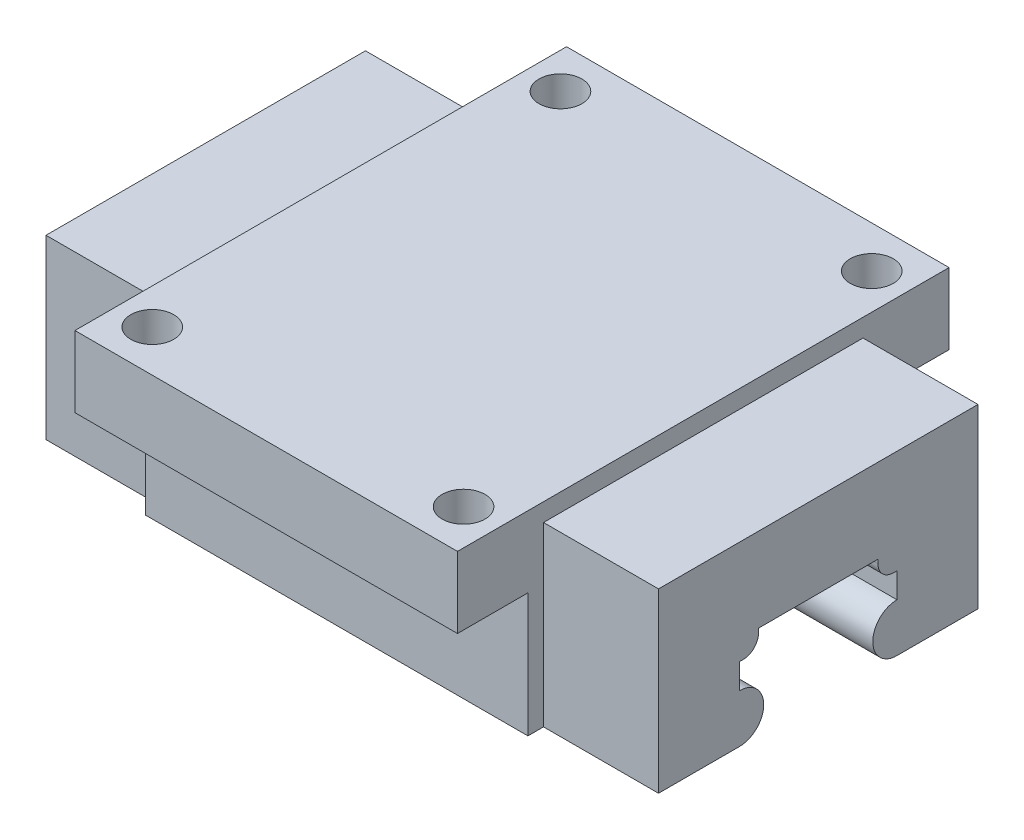
SolidWorks part; units mm, degrees
ref_plane "Plano frontal" through (0, 0, 0) normal (0, 0, 1) x (1, 0, 0)
ref_plane "Plano superior" through (0, 0, 0) normal (0, 1, 0) x (1, 0, 0)
ref_plane "Plano direito" through (0, 0, 0) normal (1, 0, 0) x (0, 0, -1)
sketch "Esboço1" plane through (0, 0, 0) normal (0, 1, 0) x (1, 0, 0)
  line L0 (-24.5155, -20.475) -> (-24.5155, -31.505)
  line L1 (-39.2555, 20.475) -> (-24.5155, 20.475)
  line L2 (-39.2555, 20.475) -> (-39.2555, -20.475)
  line L3 (-39.2555, -20.475) -> (-24.5155, -20.475)
  line L4 (39.2555, 20.475) -> (39.2555, -20.475)
  line L5 (-24.5155, 31.505) -> (24.5155, 31.505)
  line L6 (-24.5155, 31.505) -> (-24.5155, 20.475)
  line L7 (-24.5155, -31.505) -> (24.5155, -31.505)
  line L8 (24.5155, 31.505) -> (24.5155, 20.475)
  line L9 (24.5155, 20.475) -> (39.2555, 20.475)
  line L10 (24.5155, -20.475) -> (24.5155, -31.505)
  line L11 (24.5155, -20.475) -> (39.2555, -20.475)
  dimension "D1" = 40.95
  dimension "D2" = 49.0309
  dimension "D3" = 63.01
  dimension "D4" = 14.74
  dimension "D5" = 14.74
extrude "Ressalto-extrusão1" add sketch "Esboço1" against normal blind 25
sketch "Esboço2" plane through (0, 0, 0) normal (0, 1, 0) x (1, 0, 0)
  line L0 (0, 0) -> (0, -32.2621) construction
  line L1 (0, 0) -> (0, 31.505) construction
  line L2 (24.5155, 31.505) -> (-24.5155, 31.505) construction
  line L3 (0, 0) -> (39.2555, 0) construction
  line L4 (39.2555, -20.475) -> (39.2555, 20.475) construction
  line L5 (0, 0) -> (-39.2555, 0) construction
  line L6 (-39.2555, 20.475) -> (-39.2555, -20.475) construction
  circle A0 centre (-19.9505, 26.16) radius 2.75
  circle A1 centre (19.9505, 26.16) radius 2.75
  circle A2 centre (19.9505, -26.16) radius 2.75
  circle A3 centre (-19.9505, -26.16) radius 2.75
  dimension "D1" = 5.5
  dimension "D2" = 19.9505
  dimension "D3" = 5.345
  dimension "D4" = 19.305
extrude "Corte-extrusão1" cut sketch "Esboço2" against normal blind 25
sketch "Esboço3" plane through (0, 0, 0) normal (0, 1, 0) x (1, 0, 0)
  line L0 (-24.5155, 20.475) -> (-24.5155, -20.475)
  line L1 (-24.5155, -20.475) -> (-39.2555, -20.475)
  line L2 (-39.2555, -20.475) -> (-39.2555, 20.475)
  line L3 (-39.2555, 20.475) -> (-24.5155, 20.475)
  line L4 (-24.5155, 20.475) -> (-24.6983, 20.5305)
  line L5 (24.5155, 20.475) -> (24.5155, -20.475)
  line L6 (24.5155, -20.475) -> (39.2555, -20.475)
  line L7 (39.2555, -20.475) -> (39.2555, 20.475)
  line L8 (39.2555, 20.475) -> (24.5155, 20.475)
  line M5 (-39.2555, 20.475) -> (-39.2555, -20.475)
  line M6 (-39.2555, -20.475) -> (-24.5155, -20.475)
  line M10 (24.5155, -20.475) -> (39.2555, -20.475)
  line M11 (39.2555, -20.475) -> (39.2555, 20.475)
  line M12 (39.2555, 20.475) -> (24.5155, 20.475)
  line M16 (-24.5155, 20.475) -> (-39.2555, 20.475)
extrude "Corte-extrusão2" cut sketch "Esboço3" against normal blind 2.31 contours L5 M12 M10 M11 | L0 M16 M5 M6
sketch "Esboço5" plane through (-39.2555, 0, 0) normal (-1, 0, 0) x (0, 0, 1)
  line L1 (-10.088, -25) -> (10.088, -25)
  line L2 (-20.475, -25) -> (20.475, -25) construction
  line L3 (-7.649, -13.08) -> (7.649, -13.08)
  line L5 (9.6858, -15.58) -> (10.088, -15.58)
  line L6 (0, 0) -> (0, -25) construction
  line L7 (7.649, -13.08) -> (7.649, -13.5803)
  line L8 (-10.088, -18.8) -> (-10.088, -15.58)
  line L11 (10.088, -18.8) -> (10.088, -15.58)
  line L32 (-7.649, -13.08) -> (-7.649, -13.5803)
  line L33 (-9.6858, -15.58) -> (-10.088, -15.58)
  line L34 (-10.088, -15.58) -> (-10.088, -18.8)
  arc A0 (9.6858, -15.58) -> (7.649, -13.5803) centre (9.649, -13.5803) cw
  arc A1 (10.088, -25) -> (10.088, -18.8) centre (10.088, -21.9) cw
  arc A4 (-10.088, -25) -> (-10.088, -18.8) centre (-10.088, -21.9) ccw
  arc A7 (-9.6858, -15.58) -> (-7.649, -13.5803) centre (-9.649, -13.5803) ccw
  line M26 (-20.475, -25) -> (20.475, -25)
  dimension "D1" = 20.176
sketch "Esboço7" plane through (-24.5155, 0, 0) normal (-1, 0, 0) x (0, 0, 1)
  line L0 (-31.505, -25) -> (-22.475, -25)
  line L1 (-31.505, -25) -> (-20.475, -25) construction
  line L2 (-22.475, -25) -> (-22.475, -9.12)
  line L3 (-22.475, -9.12) -> (-31.505, -9.12)
  line L4 (-31.505, -25) -> (-31.505, 0) construction
  line L5 (-31.505, -9.12) -> (-31.505, -25)
  line L6 (0, 0) -> (0, -30.929) construction
  line L7 (31.505, -9.12) -> (31.505, -25)
  line L8 (22.475, -9.12) -> (31.505, -9.12)
  line L9 (22.475, -25) -> (22.475, -9.12)
  line L10 (31.505, -25) -> (22.475, -25)
  dimension "D1" = 9.12
  dimension "D2" = 2
extrude "Corte-extrusão4" cut sketch "Esboço7" against normal up to surface (49.0309 mm away)
extrude "Corte-extrusão5" cut sketch "Esboço5" against normal up to surface (78.5109 mm away) contours L6 L3 L32 A7 L33 L8 A4 M26 | L3 L6 L1 A1 L11 L5 A0 L7
